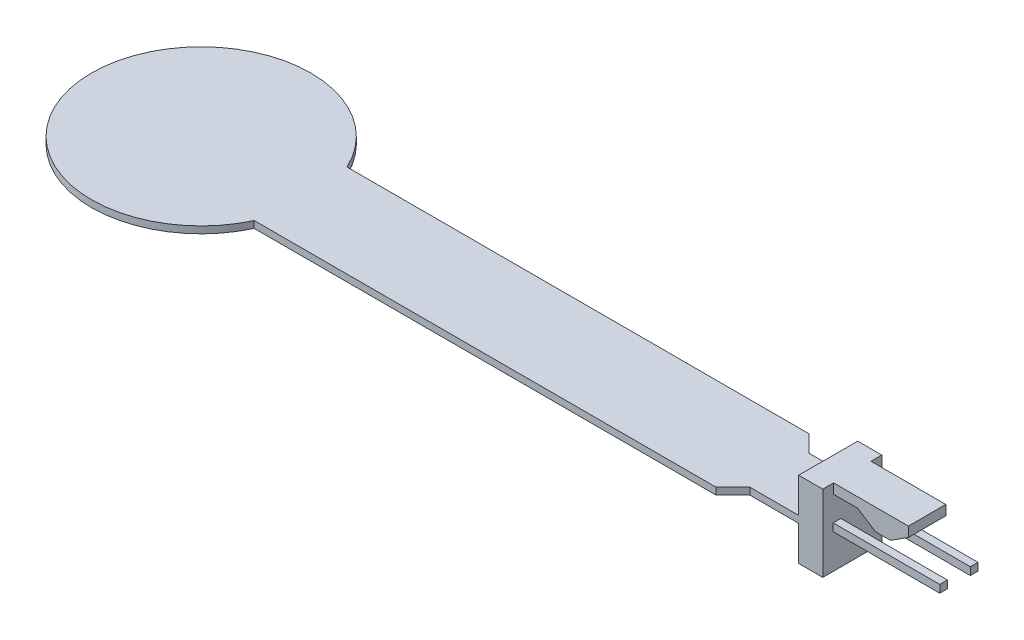
SolidWorks part; units mm, degrees
ref_plane "Front Plane" through (0, 0, 0) normal (0, 0, 1) x (1, 0, 0)
ref_plane "Top Plane" through (0, 0, 0) normal (0, 1, 0) x (1, 0, 0)
ref_plane "Right Plane" through (0, 0, 0) normal (1, 0, 0) x (0, 0, -1)
sketch "Sketch1" plane through (0, 0, 0) normal (0, 1, 0) x (1, 0, 0)
  line L0 (0, 0) -> (46.5988, 0) construction
  line L1 (8.2565, 3.85) -> (46.5988, 3.85)
  line L3 (8.2565, -3.85) -> (46.5988, -3.85)
  line L4 (46.5988, 3.85) -> (46.5988, -3.85) construction
  line L5 (0, 9.11) -> (0, -9.11) construction
  line L6 (46.5988, 3.85) -> (47.9988, 2.45)
  line L7 (47.9988, 2.45) -> (52.06, 2.45)
  line L8 (52.06, 2.45) -> (52.06, -2.45)
  line L9 (52.06, -2.45) -> (47.9988, -2.45)
  line L10 (47.9988, -2.45) -> (46.5988, -3.85)
  line L11 (46.5988, 0) -> (52.06, 0) construction
  line L12 (0, 0) -> (-9.11, 0) construction
  arc A0 (8.2565, 3.85) -> (8.2565, -3.85) centre (0, 0) ccw
  point P14 (51.2193, 2.2425)
  point P16 (48.4315, 3.85)
  point P17 (49.8046, 2.3424)
  point P18 (47.9988, 2.45)
  dimension "D1" = 18.22
  dimension "D3" = 61.17
  dimension "D2" = 7.7
  dimension "D4" = 4.9
  dimension "D5" = 45
extrude "Boss-Extrude1" add sketch "Sketch1" along normal mid plane 0.57
sketch "Sketch2" plane through (52.06, 0, 0) normal (1, 0, 0) x (0, 0, -1)
  line L0 (-2.45, -3.175) -> (2.45, 3.175) construction
  line L1 (-2.45, -3.175) -> (2.45, -3.175)
  line L2 (-2.45, -3.175) -> (-2.45, 3.175)
  line L3 (-2.45, 3.175) -> (2.45, 3.175)
  line L4 (2.45, -3.175) -> (2.45, 3.175)
  point P4 (0, 0)
  point P5 (0, 0)
  dimension "D1" = 6.35
  dimension "D2" = 4.9
extrude "Boss-Extrude2" add sketch "Sketch2" along normal blind 2
sketch "Sketch3" plane through (0, 0, 0) normal (0, 0, 1) x (1, 0, 0)
  line L0 (54.06, 3.175) -> (60.27, 3.175)
  line L1 (60.27, 3.175) -> (60.27, 2.355)
  line L2 (60.27, 2.355) -> (58.79, 1.405)
  line L3 (58.79, 1.405) -> (57.54, 1.405)
  line L4 (57.54, 1.405) -> (56.06, 2.355)
  line L5 (56.06, 2.355) -> (54.06, 2.355)
  line L6 (54.06, 3.175) -> (54.06, -3.175) construction
  line L7 (54.06, 2.355) -> (54.06, 3.175)
  line L8 (52.06, 3.175) -> (52.06, 0.285) construction
  line L9 (56.06, 2.355) -> (60.27, 2.355) construction
  line L10 (58.165, 1.405) -> (58.165, 2.355) construction
  point P14 (56.3257, 2.355)
  point P15 (57.539, 1.9958)
  dimension "D1" = 8.21
  dimension "D2" = 0.82
  dimension "D3" = 1.77
  dimension "D4" = 2
  dimension "D5" = 1.25
extrude "Boss-Extrude3" add sketch "Sketch3" along normal mid plane 3.11
sketch "Sketch4" plane through (54.06, 0, 0) normal (1, 0, 0) x (0, 0, -1)
  line L0 (-2.45, 0) -> (2.45, 0) construction
  line L1 (2.45, 0.285) -> (2.45, -0.285) construction
  line L2 (-0.9525, -0.3175) -> (0.9525, -0.3175) construction
  line L3 (-1.5875, -0.3175) -> (-0.9525, -0.3175)
  line L4 (-1.5875, -0.3175) -> (-1.5875, 0.3175)
  line L5 (-1.5875, 0.3175) -> (-0.9525, 0.3175)
  line L6 (-0.9525, -0.3175) -> (-0.9525, 0.3175)
  line L7 (-1.5875, -0.3175) -> (-0.9525, 0.3175) construction
  line L8 (-1.5875, 0.3175) -> (-0.9525, -0.3175) construction
  line L9 (0.9525, -0.3175) -> (1.5875, -0.3175)
  line L10 (0.9525, -0.3175) -> (0.9525, 0.3175)
  line L11 (0.9525, 0.3175) -> (1.5875, 0.3175)
  line L12 (1.5875, -0.3175) -> (1.5875, 0.3175)
  line L13 (0.9525, -0.3175) -> (1.5875, 0.3175) construction
  line L14 (0.9525, 0.3175) -> (1.5875, -0.3175) construction
  line L15 (0, 0) -> (0, -0.3175) construction
  point P0 (-1.27, 0)
  point P6 (0, 0)
  point P12 (1.27, 0)
  dimension "D1" = 0.635
  dimension "D2" = 2.54
extrude "Boss-Extrude4" add sketch "Sketch4" along normal offset from surface (8.85 mm away) 10.85 up to face at (52.06, 1.73, 0)
